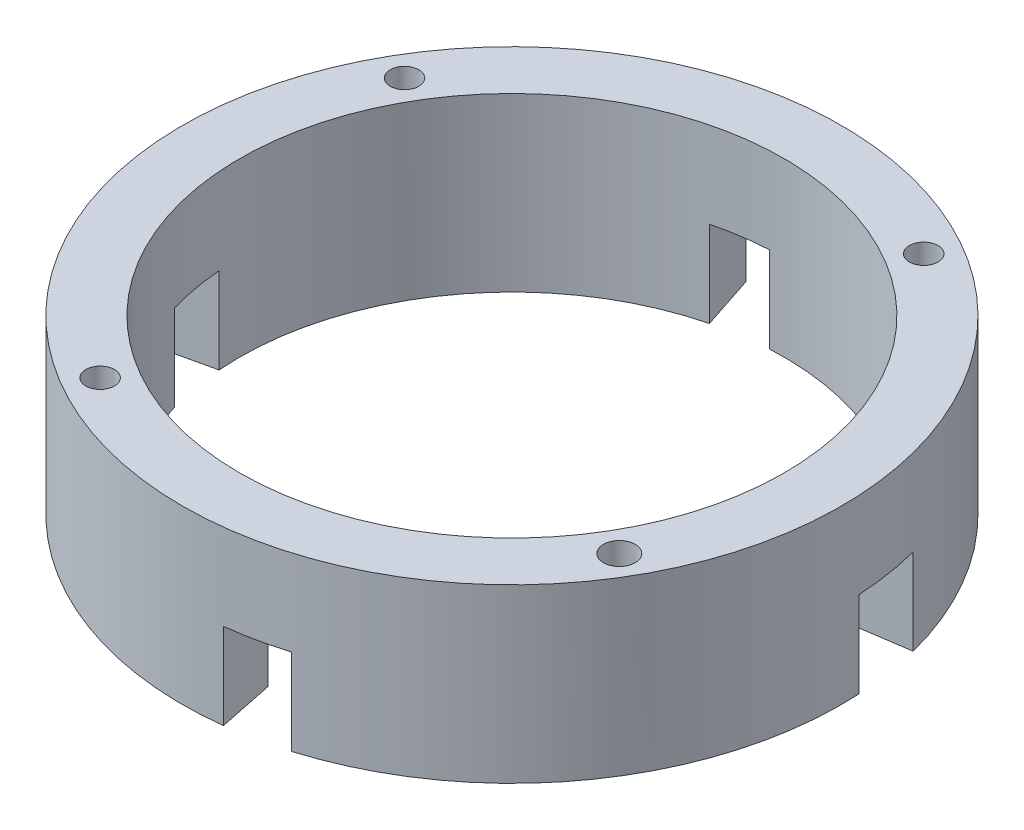
SolidWorks part; units mm, degrees
ref_plane "Plan de face" through (0, 0, 0) normal (0, 0, 1) x (1, 0, 0)
ref_plane "Plan de dessus" through (0, 0, 0) normal (0, 1, 0) x (1, 0, 0)
ref_plane "Plan de droite" through (0, 0, 0) normal (1, 0, 0) x (0, 0, -1)
sketch "Esquisse1" plane through (0, 0, 0) normal (0, 1, 0) x (1, 0, 0)
  circle A0 centre (0, 0) radius 47.5
  circle A1 centre (0, 0) radius 57.5
  dimension "D1" = 95
  dimension "D2" = 115
extrude "Boss.-Extru.3" add sketch "Esquisse1" along normal blind 30
sketch "Esquisse2" plane through (0, 30, 0) normal (0, 1, 0) x (1, 0, 0)
  line L0 (-1240.4904, -897.9912) -> (-232.4904, -897.9912) construction
sketch "Esquisse3" plane through (0, 0, 0) normal (0, -1, 0) x (1, 0, 0)
  point P0 (0, 0)
  point P4 (0, 0)
  point P5 (0, 0)
sketch "Esquisse4" plane through (0, 0, 0) normal (0, -1, 0) x (-1, 0, 0)
  line L0 (-4.7407, -47.2628) -> (-14.58, -45.207)
  line L1 (-4.7407, -47.2628) -> (-8.1599, -63.8273)
  line L2 (-14.58, -45.207) -> (-17.9991, -61.7715)
  line L3 (-8.1599, -63.8273) -> (-17.9991, -61.7715)
  circle A0 centre (0, 0) radius 47.5 construction
extrude "Enlèv. mat.-Extru.4" cut sketch "Esquisse4" against normal blind 15
sketch "Esquisse6" plane through (0, 0, 0) normal (0, -1, 0) x (-1, 0, 0)
  line L0 (37.9781, -11.4703) -> (58.7793, -16.1711)
  line L1 (37.9781, -11.4703) -> (38.9182, -1.8336)
  line L2 (58.7793, -16.1711) -> (59.7194, -6.5344)
  line L3 (38.9182, -1.8336) -> (59.7194, -6.5344)
extrude "Enlèv. mat.-Extru.5" cut sketch "Esquisse6" against normal blind 15
sketch "Esquisse7" plane through (0, 0, 0) normal (0, -1, 0) x (-1, 0, 0)
  line L0 (10.0915, 41.4768) -> (15.9395, 59.2191)
  line L1 (10.0915, 41.4768) -> (1.0717, 43.0132)
  line L2 (15.9395, 59.2191) -> (6.9197, 60.7554)
  line L3 (1.0717, 43.0132) -> (6.9197, 60.7554)
extrude "Enlèv. mat.-Extru.6" cut sketch "Esquisse7" against normal blind 15
sketch "Esquisse8" plane through (0, 0, 0) normal (0, -1, 0) x (-1, 0, 0)
  line L0 (-42.7542, 0.991) -> (-70.1633, 5.0196)
  line L1 (-42.7542, 0.991) -> (-41.4593, 12.2136)
  line L2 (-70.1633, 5.0196) -> (-68.8684, 16.2423)
  line L3 (-41.4593, 12.2136) -> (-68.8684, 16.2423)
extrude "Enlèv. mat.-Extru.7" cut sketch "Esquisse8" against normal blind 15
sketch "Esquisse10" plane through (0, 30, 0) normal (0, 1, 0) x (1, 0, 0)
  circle A0 centre (45.2891, -26.5546) radius 2.7769
  circle A2 centre (26.5546, 45.2891) radius 2.5
  circle A3 centre (-26.5546, -45.2891) radius 2.5
  circle A4 centre (-45.2891, 26.5546) radius 2.5
  point P2 (0, 0)
extrude "Enlèv. mat.-Extru.8" cut sketch "Esquisse10" against normal blind 10
